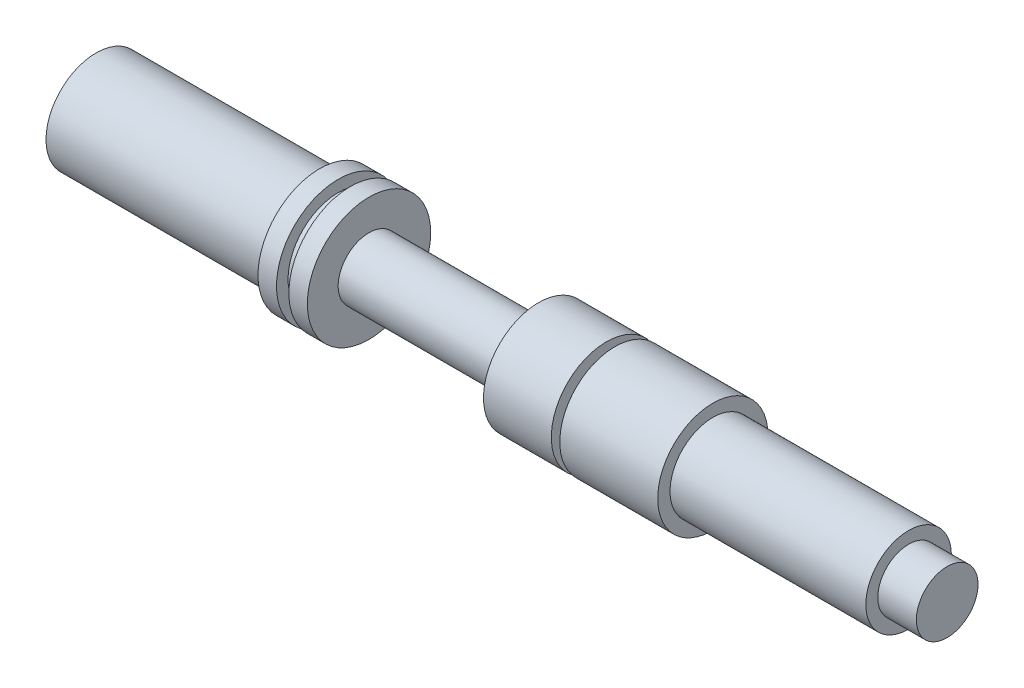
SolidWorks part; units mm, degrees
ref_plane "Спереди" through (0, 0, 0) normal (0, 0, 1) x (1, 0, 0)
ref_plane "Сверху" through (0, 0, 0) normal (0, 1, 0) x (1, 0, 0)
ref_plane "Справа" through (0, 0, 0) normal (1, 0, 0) x (0, 0, -1)
sketch "Эскиз1" plane through (0, 0, 0) normal (1, 0, 0) x (0, 0, -1)
  circle A0 centre (0, 0) radius 6.5
  dimension "D1" = 13
extrude "Бобышка-Вытянуть1" add sketch "Эскиз1" along normal blind 29
sketch "Эскиз2" plane through (29, 0, 0) normal (1, 0, 0) x (0, 0, -1)
  circle A0 centre (0, 0) radius 8
  dimension "D1" = 16
extrude "Бобышка-Вытянуть2" add sketch "Эскиз2" along normal blind 2.4
sketch "Эскиз3" plane through (31.4, 0, 0) normal (1, 0, 0) x (0, 0, -1)
  circle A0 centre (0, 0) radius 6.5
  dimension "D1" = 13
extrude "Бобышка-Вытянуть3" add sketch "Эскиз3" along normal blind 1.6
sketch "Эскиз4" plane through (33, 0, 0) normal (1, 0, 0) x (0, 0, -1)
  circle A0 centre (0, 0) radius 8
  dimension "D1" = 16
extrude "Бобышка-Вытянуть4" add sketch "Эскиз4" along normal blind 2.4
sketch "Эскиз5" plane through (35.4, 0, 0) normal (1, 0, 0) x (0, 0, -1)
  circle A0 centre (0, 0) radius 4
  dimension "D1" = 8
extrude "Бобышка-Вытянуть5" add sketch "Эскиз5" along normal blind 22
sketch "Эскиз6" plane through (57.4, 0, 0) normal (1, 0, 0) x (0, 0, -1)
  circle A0 centre (0, 0) radius 7.15
  dimension "D1" = 14.3
extrude "Бобышка-Вытянуть6" add sketch "Эскиз6" along normal blind 8.8
sketch "Эскиз7" plane through (66.2, 0, 0) normal (1, 0, 0) x (0, 0, -1)
  circle A0 centre (0, 0) radius 5.55
  dimension "D1" = 11.1
extrude "Бобышка-Вытянуть7" add sketch "Эскиз7" along normal blind 1.1
sketch "Эскиз8" plane through (67.3, 0, 0) normal (1, 0, 0) x (0, 0, -1)
  circle A0 centre (0, 0) radius 7.15
  dimension "D1" = 14.3
extrude "Бобышка-Вытянуть8" add sketch "Эскиз8" along normal blind 12.7
sketch "Эскиз9" plane through (80, 0, 0) normal (1, 0, 0) x (0, 0, -1)
  circle A0 centre (0, 0) radius 5.55
  dimension "D1" = 11.1
extrude "Бобышка-Вытянуть9" add sketch "Эскиз9" along normal blind 25.4
sketch "Эскиз10" plane through (105.4, 0, 0) normal (1, 0, 0) x (0, 0, -1)
  circle A0 centre (0, 0) radius 4
  dimension "D1" = 8
extrude "Бобышка-Вытянуть10" add sketch "Эскиз10" along normal blind 5
ref_plane "Плоскость3" through (55.2, 0, 0) normal (1, 0, 0) x (0, 0, -1)
